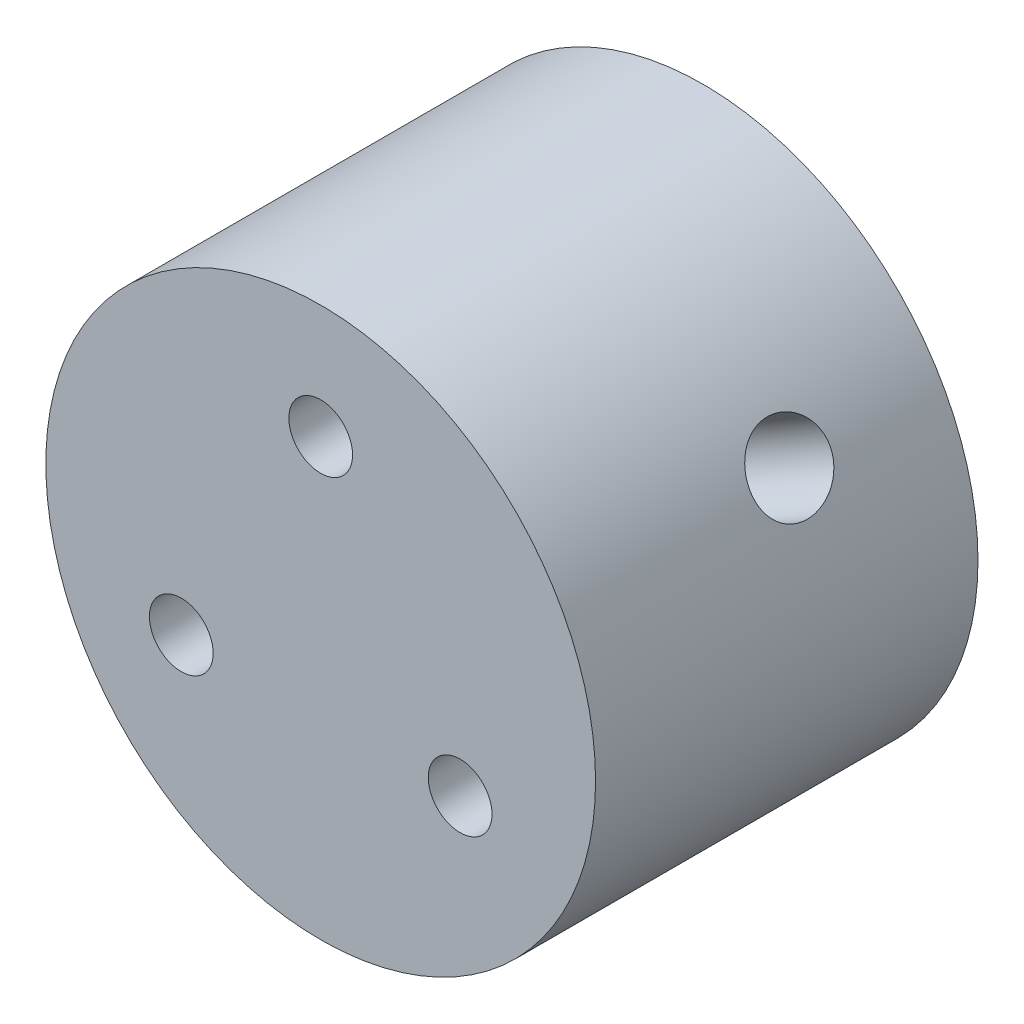
SolidWorks part; units mm, degrees
ref_plane "Přední rovina" through (0, 0, 0) normal (0, 0, 1) x (1, 0, 0)
ref_plane "Horní rovina" through (0, 0, 0) normal (0, 1, 0) x (1, 0, 0)
ref_plane "Pravá rovina" through (0, 0, 0) normal (1, 0, 0) x (0, 0, -1)
sketch "Skica1" plane through (0, 0, 0) normal (0, 0, 1) x (1, 0, 0)
  circle A0 centre (0, 0) radius 34.5
  dimension "D1" = 69
extrude "Přidat vysunutím1" add sketch "Skica1" along normal blind 48
sketch "Skica2" plane through (0, 0, 48) normal (0, 0, 1) x (1, 0, 0)
  line L1 (0, 20.2073) -> (-17.5, -10.1036) construction
  line L2 (-17.5, -10.1036) -> (17.5, -10.1036) construction
  line L3 (17.5, -10.1036) -> (0, 20.2073) construction
  circle A0 centre (0, 0) radius 10.1036 construction
  circle A1 centre (0, 20.2073) radius 4
  circle A2 centre (17.5, -10.1036) radius 4
  circle A3 centre (-17.5, -10.1036) radius 4
  dimension "D2" = 8
  dimension "D1" = 35
extrude "Odebrat vysunutím1" cut sketch "Skica2" against normal blind 40
sketch "Skica3" plane through (0, 0, 0) normal (0, 1, 0) x (1, 0, 0)
  line L0 (0, 0) -> (0, -42.7972) construction
  circle A0 centre (0, -19) radius 5
  dimension "D1" = 10
  dimension "D2" = 19
extrude "Odebrat vysunutím2" cut sketch "Skica3" against normal through all
pattern_circular "Kruhové pole1" count 3 over 360 about axis through (0, 0, 48) along (0, 0, -1) of "Odebrat vysunutím2"
